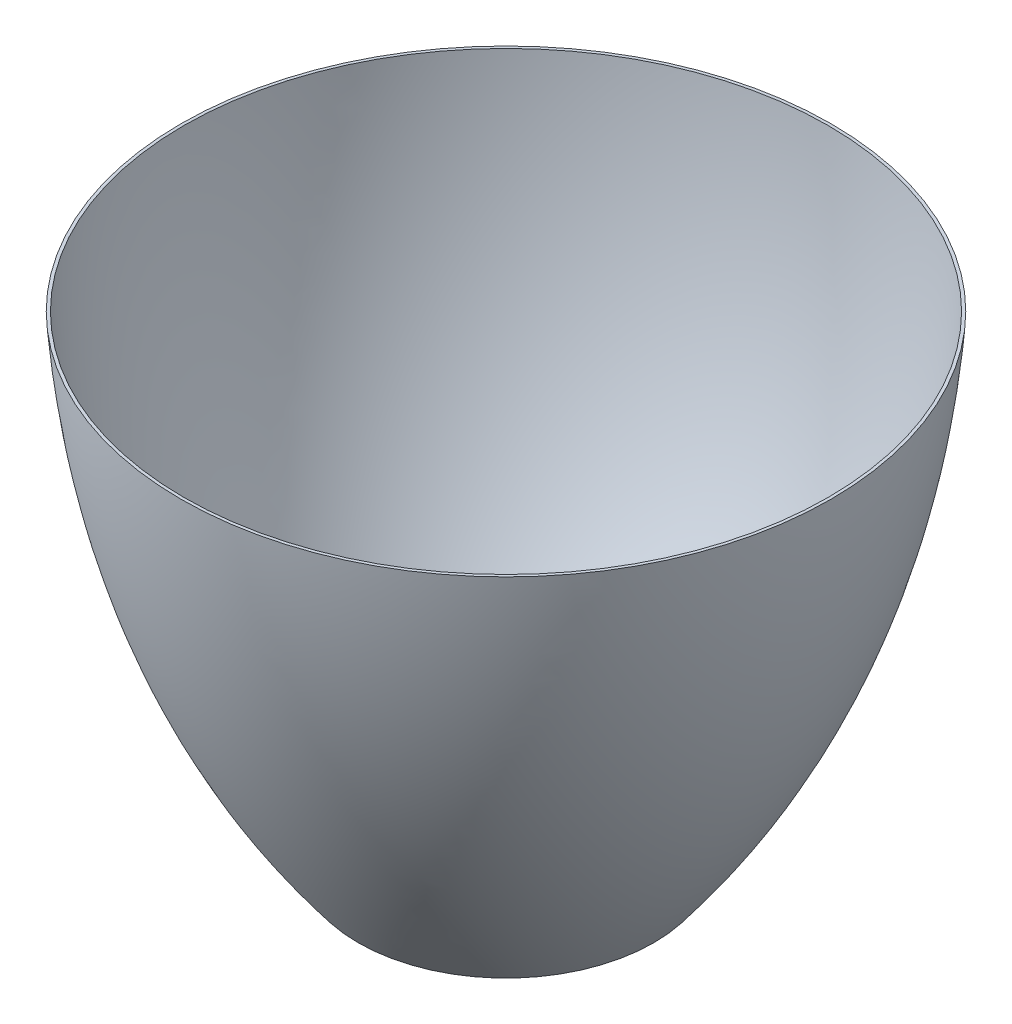
SolidWorks part; units mm, degrees
ref_plane "正面" through (0, 0, 0) normal (0, 0, 1) x (1, 0, 0)
ref_plane "平面" through (0, 0, 0) normal (0, 1, 0) x (1, 0, 0)
ref_plane "右側面" through (0, 0, 0) normal (1, 0, 0) x (0, 0, -1)
sketch "ｽｹｯﾁ1" plane through (0, 0, 0) normal (0, 0, 1) x (1, 0, 0)
  line L0 (0, 80) -> (0, 0)
  line L1 (0, 0) -> (25, 0)
  line L2 (0, 80) -> (55, 80)
  spline S0 degree 2 poles (25, 0) (51.409, 34.4065) (55, 80) knots 0 0 0 1 1 1
  point P6 (42.4961, 51.8798)
  point P7 (33.5076, 12.3252)
  point P8 (39.4761, 21.4638)
  point P9 (0, 0)
  point P10 (43.1433, 56.1941)
  point P11 (33.9005, 19.6463)
  point P12 (42.3205, 54.4966)
  point P13 (50.9705, 64.9042)
  point P14 (0, 0)
  point P15 (0, 0)
  dimension "D1" = 80
  dimension "D2" = 25
  dimension "D3" = 55
revolve "回転1" add sketch "ｽｹｯﾁ1" angle 360 about L0
shell "ｼｪﾙ1" thickness 0.5
